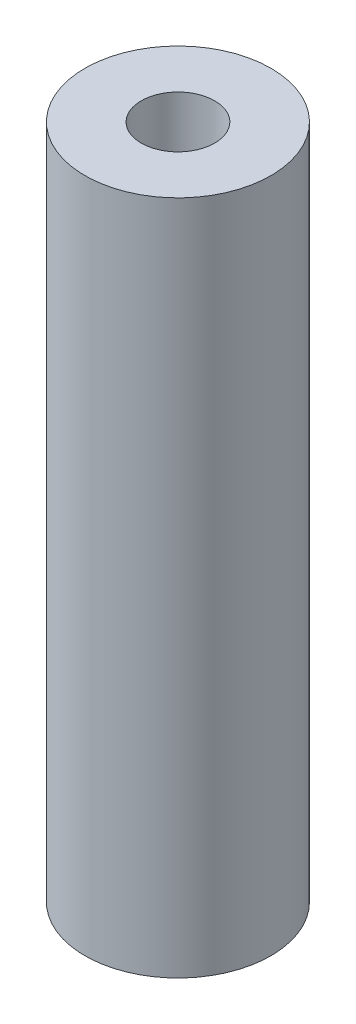
SolidWorks part; units mm, degrees
material "Nylon 101"
ref_plane "Front Plane" through (0, 0, 0) normal (0, 0, 1) x (1, 0, 0)
ref_plane "Top Plane" through (0, 0, 0) normal (0, 1, 0) x (1, 0, 0)
ref_plane "Right Plane" through (0, 0, 0) normal (1, 0, 0) x (0, 0, -1)
sketch "Sketch2" plane through (0, 0, 0) normal (0, 1, 0) x (1, 0, 0)
  circle A0 centre (0, 0) radius 5.2451
  circle A1 centre (0, 0) radius 2.0701
  dimension "D1" = 4.1402
  dimension "D2" = 3.175
extrude "Boss-Extrude1" add sketch "Sketch2" along normal mid plane 38.1
